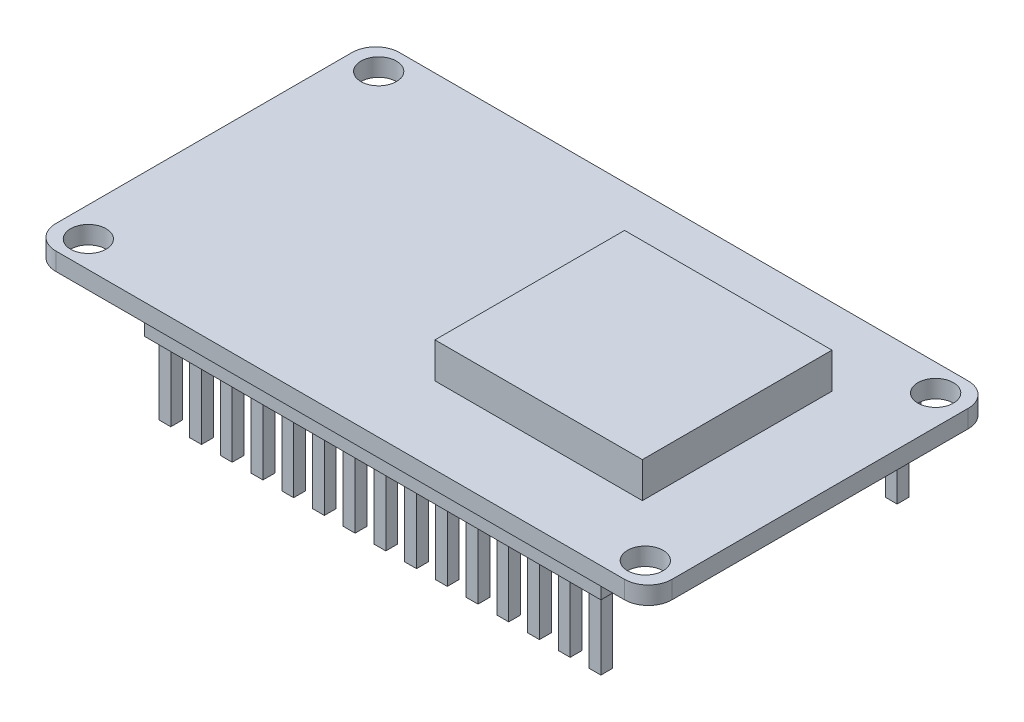
SolidWorks part; units mm, degrees
ref_plane "Front Plane" through (0, 0, 0) normal (0, 0, 1) x (1, 0, 0)
ref_plane "Top Plane" through (0, 0, 0) normal (0, 1, 0) x (1, 0, 0)
ref_plane "Right Plane" through (0, 0, 0) normal (1, 0, 0) x (0, 0, -1)
sketch "Sketch1" plane through (0, 0, 0) normal (0, 1, 0) x (1, 0, 0)
  line L0 (0, 8.1956) -> (0, 0) construction
  line L1 (24, -14.5) -> (-24, -14.5)
  line L2 (26, -12.5) -> (26, 12.5)
  line L3 (24, 14.5) -> (-24, 14.5)
  line L4 (-26, -12.5) -> (-26, 12.5)
  line L5 (26, -14.5) -> (-26, 14.5) construction
  line L6 (26, 14.5) -> (-26, -14.5) construction
  line L7 (0, 0) -> (12.3915, 0) construction
  circle A0 centre (-23.5, 12.25) radius 1.5
  circle A1 centre (23.5, 12.25) radius 1.5
  circle A2 centre (23.5, -12.25) radius 1.5
  circle A3 centre (-23.5, -12.25) radius 1.5
  arc A4 (26, 12.5) -> (24, 14.5) centre (24, 12.5) ccw
  arc A5 (24, -14.5) -> (26, -12.5) centre (24, -12.5) ccw
  arc A6 (-24, -14.5) -> (-26, -12.5) centre (-24, -12.5) cw
  arc A7 (-24, 14.5) -> (-26, 12.5) centre (-24, 12.5) ccw
  point P0 (0, 0)
  dimension "D3" = 3
  dimension "D6" = 2
  dimension "D1" = 52
  dimension "D2" = 29
  dimension "D4" = 2.25
  dimension "D5" = 2.5
extrude "Boss-Extrude1" add sketch "Sketch1" along normal blind 1.5
sketch "Sketch2" plane through (0, 0, 0) normal (0, 1, 0) x (1, 0, 0)
  line L0 (26, -12.5) -> (26, 12.5) construction
  line L1 (-17.5, -11.5) -> (21, -11.5)
  line L2 (-17.5, -11.5) -> (-17.5, -13.5)
  line L3 (-17.5, -13.5) -> (21, -13.5)
  line L4 (21, -11.5) -> (21, -13.5)
  line L5 (-24, -14.5) -> (24, -14.5) construction
  line L6 (0, 0) -> (13.5888, 0) construction
  line L7 (-17.5, 13.5) -> (21, 13.5)
  line L8 (21, 11.5) -> (21, 13.5)
  line L9 (-17.5, 11.5) -> (21, 11.5)
  line L10 (-17.5, 11.5) -> (-17.5, 13.5)
  dimension "D1" = 2
  dimension "D2" = 38.5
  dimension "D3" = 5
  dimension "D4" = 1
extrude "Boss-Extrude2" add sketch "Sketch2" against normal blind 2
sketch "Sketch3" plane through (0, 1.5, 0) normal (0, 1, 0) x (1, 0, 0)
  line L0 (26, -12.5) -> (26, 12.5) construction
  line L1 (1.5, 8) -> (19, 8)
  line L2 (1.5, 8) -> (1.5, -8)
  line L3 (1.5, -8) -> (19, -8)
  line L4 (19, 8) -> (19, -8)
  line L5 (1.5, 8) -> (19, -8) construction
  line L6 (1.5, -8) -> (19, 8) construction
  point P0 (10.25, 0)
  point P8 (0, 0)
  dimension "D1" = 17.5
  dimension "D2" = 16
  dimension "D3" = 7
extrude "Boss-Extrude3" add sketch "Sketch3" along normal blind 3
sketch "Sketch4" plane through (0, 0, 0) normal (0, 1, 0) x (1, 0, 0)
  line L0 (21, 12.5) -> (-17.5, 12.5) construction
  line L1 (21, 11.5) -> (21, 13.5) construction
  line L2 (-17.5, 13.5) -> (-17.5, 11.5) construction
  line L3 (21, 11.5) -> (21, 13.5) construction
  line L4 (19.5, 12) -> (20.5, 12)
  line L5 (19.5, 12) -> (19.5, 13)
  line L6 (19.5, 13) -> (20.5, 13)
  line L7 (20.5, 12) -> (20.5, 13)
  line L8 (19.5, 12) -> (20.5, 13) construction
  line L9 (19.5, 13) -> (20.5, 12) construction
  line L10 (16.9075, 12) -> (16.9075, 13)
  line L11 (16.9075, 12) -> (17.9075, 12)
  line L12 (17.9075, 12) -> (17.9075, 13)
  line L13 (16.9075, 13) -> (17.9075, 13)
  line L14 (14.315, 12) -> (14.315, 13)
  line L15 (14.315, 12) -> (15.315, 12)
  line L16 (15.315, 12) -> (15.315, 13)
  line L17 (14.315, 13) -> (15.315, 13)
  line L18 (11.7225, 12) -> (11.7225, 13)
  line L19 (11.7225, 12) -> (12.7225, 12)
  line L20 (12.7225, 12) -> (12.7225, 13)
  line L21 (11.7225, 13) -> (12.7225, 13)
  line L22 (9.13, 12) -> (9.13, 13)
  line L23 (9.13, 12) -> (10.13, 12)
  line L24 (10.13, 12) -> (10.13, 13)
  line L25 (9.13, 13) -> (10.13, 13)
  line L26 (6.5375, 12) -> (6.5375, 13)
  line L27 (6.5375, 12) -> (7.5375, 12)
  line L28 (7.5375, 12) -> (7.5375, 13)
  line L29 (6.5375, 13) -> (7.5375, 13)
  line L30 (3.945, 12) -> (3.945, 13)
  line L31 (3.945, 12) -> (4.945, 12)
  line L32 (4.945, 12) -> (4.945, 13)
  line L33 (3.945, 13) -> (4.945, 13)
  line L34 (1.3525, 12) -> (1.3525, 13)
  line L35 (1.3525, 12) -> (2.3525, 12)
  line L36 (2.3525, 12) -> (2.3525, 13)
  line L37 (1.3525, 13) -> (2.3525, 13)
  line L38 (-1.24, 12) -> (-1.24, 13)
  line L39 (-1.24, 12) -> (-0.24, 12)
  line L40 (-0.24, 12) -> (-0.24, 13)
  line L41 (-1.24, 13) -> (-0.24, 13)
  line L42 (-3.8325, 12) -> (-3.8325, 13)
  line L43 (-3.8325, 12) -> (-2.8325, 12)
  line L44 (-2.8325, 12) -> (-2.8325, 13)
  line L45 (-3.8325, 13) -> (-2.8325, 13)
  line L46 (-6.425, 12) -> (-6.425, 13)
  line L47 (-6.425, 12) -> (-5.425, 12)
  line L48 (-5.425, 12) -> (-5.425, 13)
  line L49 (-6.425, 13) -> (-5.425, 13)
  line L50 (-9.0175, 12) -> (-9.0175, 13)
  line L51 (-9.0175, 12) -> (-8.0175, 12)
  line L52 (-8.0175, 12) -> (-8.0175, 13)
  line L53 (-9.0175, 13) -> (-8.0175, 13)
  line L54 (-11.61, 12) -> (-11.61, 13)
  line L55 (-11.61, 12) -> (-10.61, 12)
  line L56 (-10.61, 12) -> (-10.61, 13)
  line L57 (-11.61, 13) -> (-10.61, 13)
  line L58 (-14.2025, 12) -> (-14.2025, 13)
  line L59 (-14.2025, 12) -> (-13.2025, 12)
  line L60 (-13.2025, 12) -> (-13.2025, 13)
  line L61 (-14.2025, 13) -> (-13.2025, 13)
  line L62 (-16.795, 12) -> (-16.795, 13)
  line L63 (-16.795, 12) -> (-15.795, 12)
  line L64 (-15.795, 12) -> (-15.795, 13)
  line L65 (-16.795, 13) -> (-15.795, 13)
  line L66 (0, 0) -> (-12.6437, 0) construction
  line L67 (19.5, -13) -> (20.5, -12) construction
  line L68 (19.5, -12) -> (20.5, -13) construction
  line L69 (21, -12.5) -> (-17.5, -12.5) construction
  line L70 (-16.795, -13) -> (-15.795, -13)
  line L71 (-15.795, -12) -> (-15.795, -13)
  line L72 (-16.795, -12) -> (-15.795, -12)
  line L73 (-16.795, -12) -> (-16.795, -13)
  line L74 (-14.2025, -13) -> (-13.2025, -13)
  line L75 (-13.2025, -12) -> (-13.2025, -13)
  line L76 (-14.2025, -12) -> (-13.2025, -12)
  line L77 (-14.2025, -12) -> (-14.2025, -13)
  line L78 (-11.61, -13) -> (-10.61, -13)
  line L79 (-10.61, -12) -> (-10.61, -13)
  line L80 (-11.61, -12) -> (-10.61, -12)
  line L81 (-11.61, -12) -> (-11.61, -13)
  line L82 (-9.0175, -13) -> (-8.0175, -13)
  line L83 (-8.0175, -12) -> (-8.0175, -13)
  line L84 (-9.0175, -12) -> (-8.0175, -12)
  line L85 (-9.0175, -12) -> (-9.0175, -13)
  line L86 (-6.425, -13) -> (-5.425, -13)
  line L87 (-5.425, -12) -> (-5.425, -13)
  line L88 (-6.425, -12) -> (-5.425, -12)
  line L89 (-6.425, -12) -> (-6.425, -13)
  line L90 (-3.8325, -13) -> (-2.8325, -13)
  line L91 (-2.8325, -12) -> (-2.8325, -13)
  line L92 (-3.8325, -12) -> (-2.8325, -12)
  line L93 (-3.8325, -12) -> (-3.8325, -13)
  line L94 (-1.24, -13) -> (-0.24, -13)
  line L95 (-0.24, -12) -> (-0.24, -13)
  line L96 (-1.24, -12) -> (-0.24, -12)
  line L97 (-1.24, -12) -> (-1.24, -13)
  line L98 (1.3525, -13) -> (2.3525, -13)
  line L99 (2.3525, -12) -> (2.3525, -13)
  line L100 (1.3525, -12) -> (2.3525, -12)
  line L101 (1.3525, -12) -> (1.3525, -13)
  line L102 (3.945, -13) -> (4.945, -13)
  line L103 (4.945, -12) -> (4.945, -13)
  line L104 (3.945, -12) -> (4.945, -12)
  line L105 (3.945, -12) -> (3.945, -13)
  line L106 (6.5375, -13) -> (7.5375, -13)
  line L107 (7.5375, -12) -> (7.5375, -13)
  line L108 (6.5375, -12) -> (7.5375, -12)
  line L109 (6.5375, -12) -> (6.5375, -13)
  line L110 (9.13, -13) -> (10.13, -13)
  line L111 (10.13, -12) -> (10.13, -13)
  line L112 (9.13, -12) -> (10.13, -12)
  line L113 (9.13, -12) -> (9.13, -13)
  line L114 (11.7225, -13) -> (12.7225, -13)
  line L115 (12.7225, -12) -> (12.7225, -13)
  line L116 (11.7225, -12) -> (12.7225, -12)
  line L117 (11.7225, -12) -> (11.7225, -13)
  line L118 (14.315, -13) -> (15.315, -13)
  line L119 (15.315, -12) -> (15.315, -13)
  line L120 (14.315, -12) -> (15.315, -12)
  line L121 (14.315, -12) -> (14.315, -13)
  line L122 (16.9075, -13) -> (17.9075, -13)
  line L123 (17.9075, -12) -> (17.9075, -13)
  line L124 (16.9075, -12) -> (17.9075, -12)
  line L125 (16.9075, -12) -> (16.9075, -13)
  line L126 (20.5, -12) -> (20.5, -13)
  line L127 (19.5, -13) -> (20.5, -13)
  line L128 (19.5, -12) -> (19.5, -13)
  line L129 (19.5, -12) -> (20.5, -12)
  line L131 (-17.5, 11.5) -> (21, 11.5) construction
  point P6 (20, 12.5)
  point P134 (20, -12.5)
  point P137 (0, 0)
  point P140 (0, 0)
  dimension "D1" = 1
  dimension "D2" = 1
  dimension "D3" = 0.5
  dimension "D5" = 11.5
  dimension "D4" = 15
extrude "Boss-Extrude4" add sketch "Sketch4" against normal blind 8
